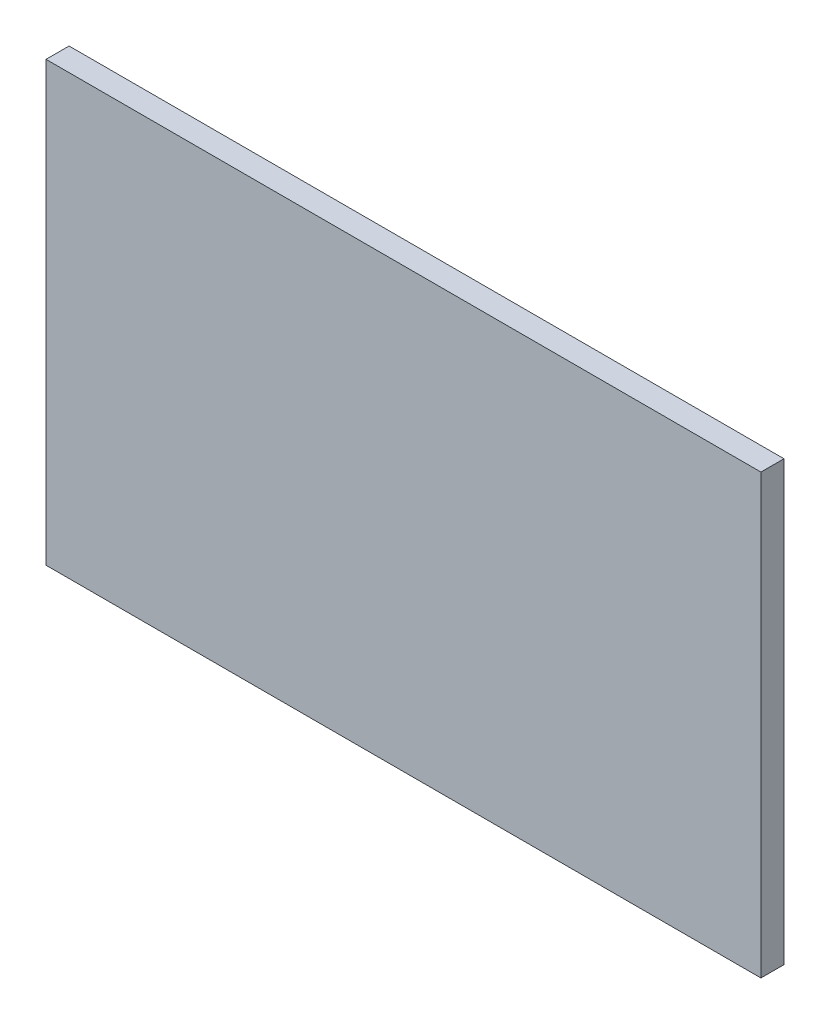
SolidWorks part; units mm, degrees
ref_plane "Front Plane" through (0, 0, 0) normal (0, 0, 1) x (1, 0, 0)
ref_plane "Top Plane" through (0, 0, 0) normal (0, 1, 0) x (1, 0, 0)
ref_plane "Right Plane" through (0, 0, 0) normal (1, 0, 0) x (0, 0, -1)
sketch "Sketch1" plane through (0, 0, 0) normal (0, 0, 1) x (1, 0, 0)
  line L1 (15.5, -9.5) -> (-15.5, -9.5)
  line L2 (15.5, -9.5) -> (15.5, 9.5)
  line L3 (15.5, 9.5) -> (-15.5, 9.5)
  line L4 (-15.5, -9.5) -> (-15.5, 9.5)
  line L5 (0, 9.5) -> (0, -9.5) construction
  line L6 (15.5, 0) -> (-15.5, 0) construction
  point P0 (0, 0)
  dimension "D1" = 19
  dimension "D2" = 31
extrude "Boss-Extrude1" add sketch "Sketch1" along normal blind 1 contours L2 L1 L4 L3
